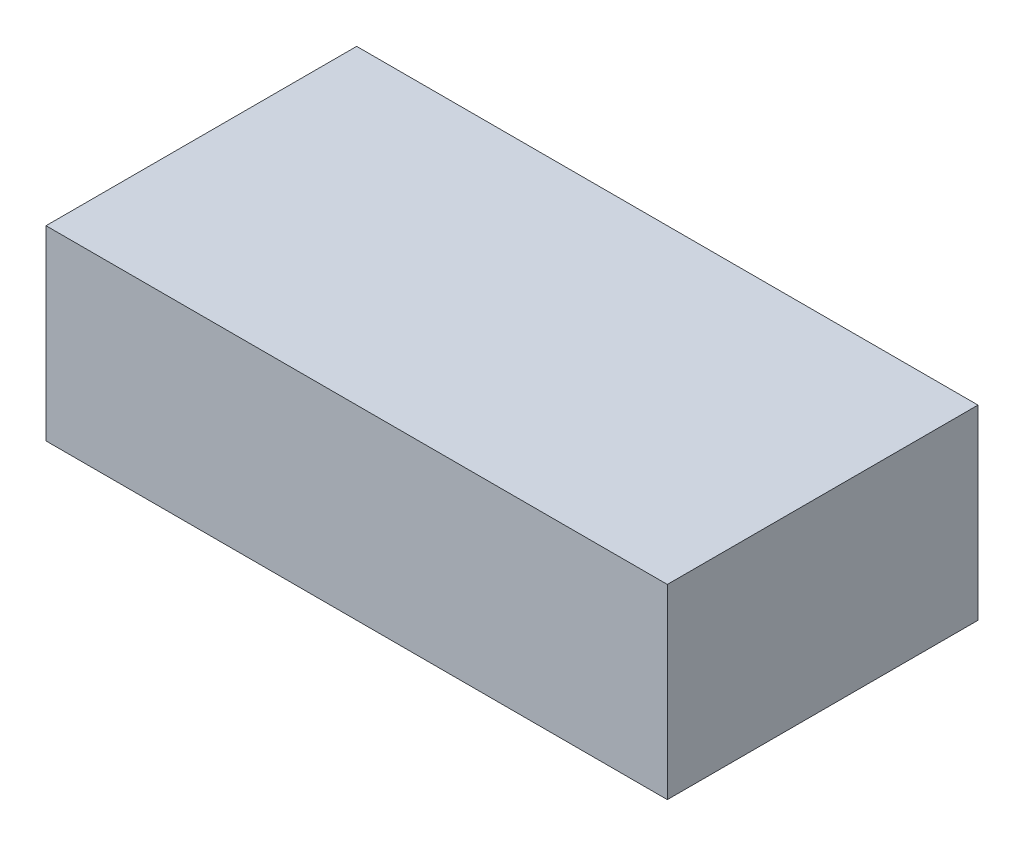
SolidWorks part; units mm, degrees
ref_plane "Front Plane" through (0, 0, 0) normal (0, 0, 1) x (1, 0, 0)
ref_plane "Top Plane" through (0, 0, 0) normal (0, 1, 0) x (1, 0, 0)
ref_plane "Right Plane" through (0, 0, 0) normal (1, 0, 0) x (0, 0, -1)
sketch "Sketch1" plane through (0, 0, 0) normal (0, 1, 0) x (1, 0, 0)
  line L1 (-50, -25) -> (50, -25)
  line L2 (-50, -25) -> (-50, 25)
  line L3 (-50, 25) -> (50, 25)
  line L4 (50, -25) -> (50, 25)
  line L5 (-50, -25) -> (50, 25) construction
  line L6 (-50, 25) -> (50, -25) construction
  point P0 (0, 0)
  dimension "D1" = 50
  dimension "D2" = 100
extrude "Boss-Extrude1" add sketch "Sketch1" along normal blind 30
equation "\"length\" = 100"
equation "\"width\"=50"
equation "\"height\"= 30"
equation "\"D1@Sketch1\"=\"width\""
equation "\"D2@Sketch1\"=\"length\""
equation "\"D1@Boss-Extrude1\"=\"height\""
